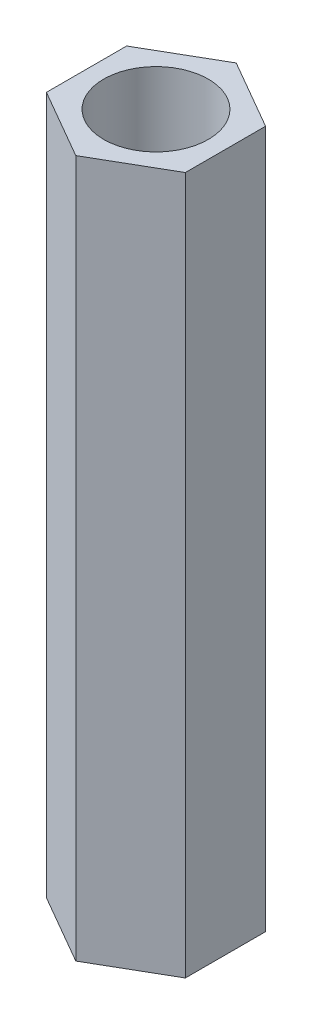
SolidWorks part; units mm, degrees
material "黄铜"
ref_plane "前视基准面" through (0, 0, 0) normal (0, 0, 1) x (1, 0, 0)
ref_plane "上视基准面" through (0, 0, 0) normal (0, 1, 0) x (1, 0, 0)
ref_plane "右视基准面" through (0, 0, 0) normal (1, 0, 0) x (0, 0, -1)
other "Configuration Table"
sketch "草图1" plane through (0, 0, 0) normal (0, 1, 0) x (1, 0, 0)
  line L0 (0, 0) -> (0, 3.0947) construction
  line L1 (1.9919, 1.15) -> (0, 2.3)
  line L2 (0, 2.3) -> (-1.9919, 1.15)
  line L3 (-1.9919, 1.15) -> (-1.9919, -1.15)
  line L4 (-1.9919, -1.15) -> (0, -2.3)
  line L5 (0, -2.3) -> (1.9919, -1.15)
  line L6 (1.9919, -1.15) -> (1.9919, 1.15)
  circle A0 centre (0, 0) radius 1.5
  circle A1 centre (0, 0) radius 1.9919 construction
  dimension "D1" = 3
  dimension "D2" = 4.6
extrude "凸台-拉伸1" add sketch "草图1" along normal blind 20
